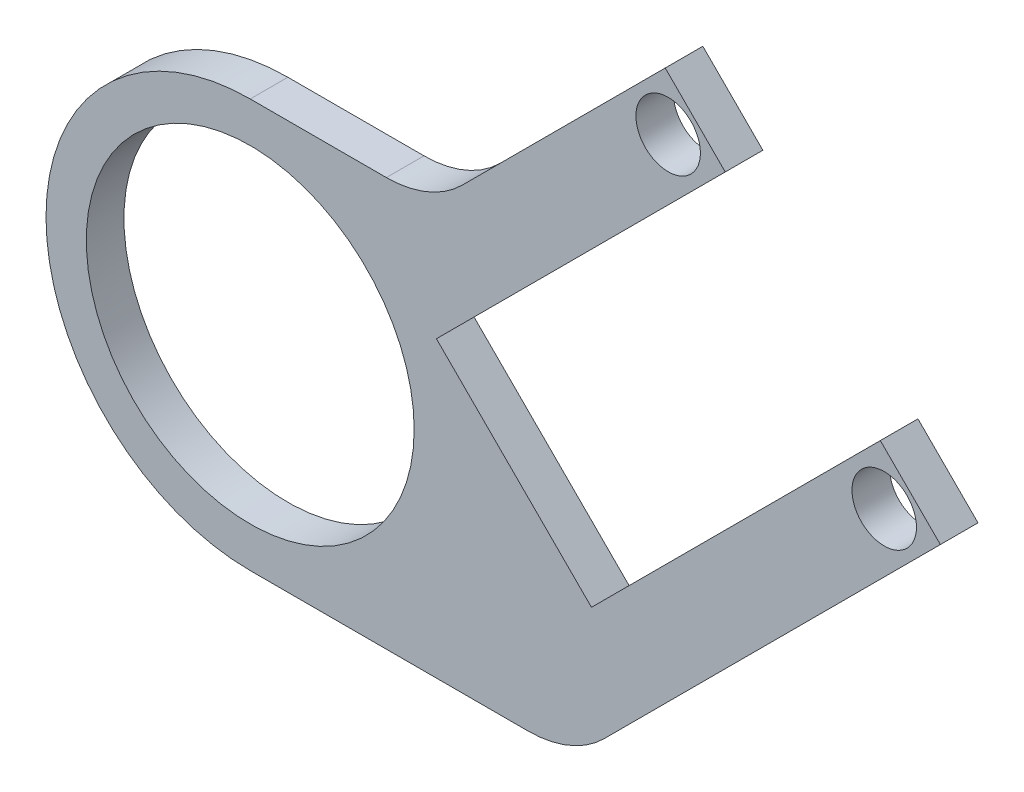
SolidWorks part; units mm, degrees
material "Foam"
ref_plane "Front Plane" through (0, 0, 0) normal (0, 0, 1) x (1, 0, 0)
ref_plane "Top Plane" through (0, 0, 0) normal (0, 1, 0) x (1, 0, 0)
ref_plane "Right Plane" through (0, 0, 0) normal (1, 0, 0) x (0, 0, -1)
sketch "Sketch1" plane through (0, 0, 0) normal (0, 0, 1) x (1, 0, 0)
  line L0 (51.4027, 28) -> (24.5327, 1.1299) construction
  line L1 (0, -19) -> (30, -19)
  line L2 (17.3202, 8.3424) -> (31.7452, -6.0825)
  line L3 (31.7452, -6.0825) -> (58.6152, 20.7875)
  line L4 (17.3202, 8.3424) -> (44.1902, 35.2125)
  line L5 (30, -19) -> (64.2014, 15.2014)
  line L6 (44.1902, 35.2125) -> (58.6152, 20.7875) construction
  line L7 (64.2014, 15.2014) -> (58.6152, 20.7875)
  line L8 (0, 0) -> (0, 28) construction
  line L9 (44.1902, 35.2125) -> (38.6041, 40.7986)
  line L10 (38.6041, 40.7986) -> (16.8055, 19)
  line L11 (16.8055, 19) -> (0, 19)
  line L12 (0, 0) -> (-19, 0) construction
  line L13 (51.4027, 28) -> (0, 28) construction
  arc A0 (0, 19) -> (0, -19) centre (0, 0) ccw
  circle A1 centre (0, 0) radius 2.5
  dimension "D5" = 5
  dimension "D4" = 36.2
  dimension "D8" = 30
  dimension "D7" = 28
  dimension "D1" = 38
  dimension "D2" = 20.4
  dimension "D3" = 38
  dimension "D6" = 45
extrude "Boss-Extrude1" add sketch "Sketch1" along normal blind 3.5
sketch "Sketch2" plane through (0, 0, 3.5) normal (0, 0, 1) x (1, 0, 0)
  line L0 (44.1902, 35.2125) -> (38.6041, 40.7986) construction
  line L1 (44.1902, 35.2125) -> (58.6152, 20.7875) construction
  line L3 (24.5327, 1.1299) -> (51.4027, 28) construction
  line L4 (31.7452, -6.0825) -> (17.3202, 8.3424) construction
  circle A0 centre (38.8781, 35.5749) radius 1.5
  circle A1 centre (58.9776, 15.4754) radius 1.5
  dimension "D1" = 3
  dimension "D2" = 3.5
  dimension "D3" = 28.425
extrude "Cut-Extrude1" cut sketch "Sketch2" against normal through all
fillet "Fillet1" radius 10 2 edges at (16.8055, 19, 1.75) (30, -19, 1.75)
sketch "Sketch5" plane through (0, 0, 3.5) normal (0, 0, 1) x (1, 0, 0)
  circle A0 centre (0, 0) radius 15.25
  circle A1 centre (38.8781, 35.5749) radius 3
  circle A2 centre (58.9776, 15.4754) radius 3
  dimension "D1" = 30.5
  dimension "D2" = 6
extrude "Cut-Extrude4" cut sketch "Sketch5" against normal through all
equation "\"D2@Sketch1\"=20.20mm+\"cut_free@Parameters@Parameters.SLDPRT\""
